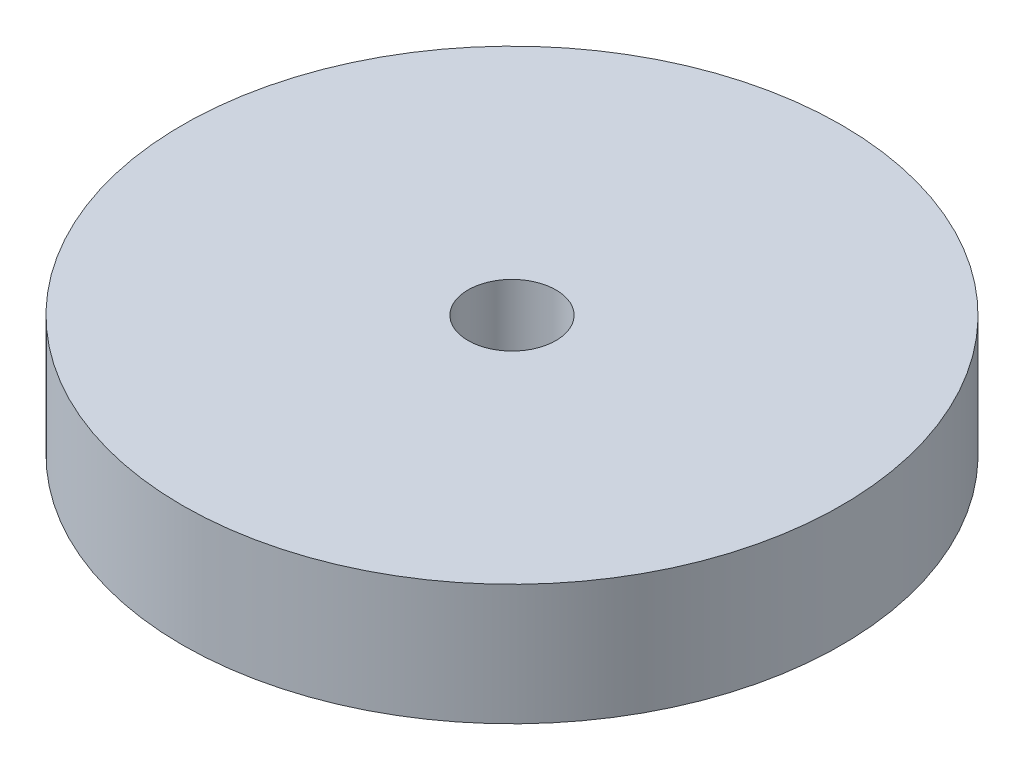
SolidWorks part; units mm, degrees
ref_plane "正面" through (0, 0, 0) normal (0, 0, 1) x (1, 0, 0)
ref_plane "平面" through (0, 0, 0) normal (0, 1, 0) x (1, 0, 0)
ref_plane "右側面" through (0, 0, 0) normal (1, 0, 0) x (0, 0, -1)
sketch "ｽｹｯﾁ1" plane through (0, 0, 0) normal (0, 1, 0) x (1, 0, 0)
  circle A0 centre (0, 0) radius 15
  dimension "D1" = 30
extrude "ﾎﾞｽ - 押し出し1" add sketch "ｽｹｯﾁ1" along normal blind 5.5
sketch "ｽｹｯﾁ2" plane through (0, 5.5, 0) normal (0, 1, 0) x (1, 0, 0)
  circle A0 centre (0, 0) radius 2
  dimension "D1" = 4
extrude "ｶｯﾄ - 押し出し1" cut sketch "ｽｹｯﾁ2" against normal through all
